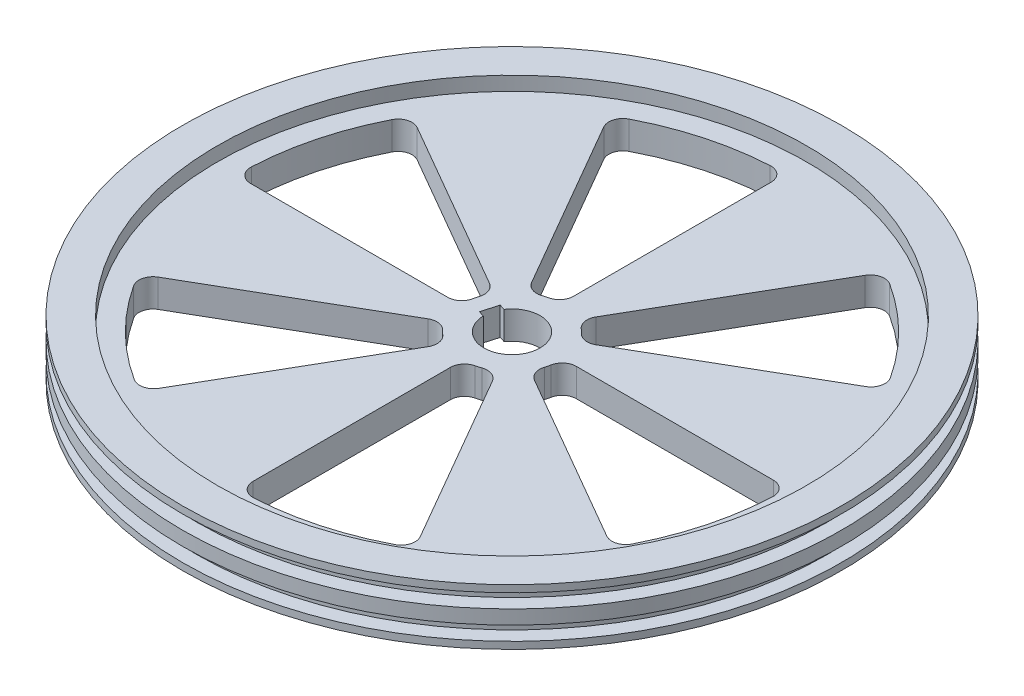
SolidWorks part; units mm, degrees
material "1023 Carbon Steel Sheet (SS)"
ref_plane "Front Plane" through (0, 0, 0) normal (0, 0, 1) x (1, 0, 0)
ref_plane "Top Plane" through (0, 0, 0) normal (0, 1, 0) x (1, 0, 0)
ref_plane "Right Plane" through (0, 0, 0) normal (1, 0, 0) x (0, 0, -1)
sketch "Sketch1" plane through (0, 0, 0) normal (1, 0, 0) x (0, 0, -1)
  line L0 (0, 0) -> (0, 76.2243) construction
  line L1 (20, 0) -> (20, 40)
  line L2 (20, 0) -> (235, 0)
  line L3 (235, 0) -> (235, 5)
  line L4 (235, 5) -> (225, 5)
  line L5 (225, 5) -> (225, 15)
  line L6 (225, 15) -> (235, 15)
  line L7 (235, 15) -> (235, 25)
  line L8 (235, 25) -> (225, 25)
  line L9 (225, 25) -> (225, 35)
  line L10 (225, 35) -> (235, 35)
  line L11 (235, 35) -> (235, 40)
  line L12 (235, 40) -> (20, 40)
  point P11 (225, 30)
  dimension "D1" = 20
  dimension "D2" = 225
revolve "Revolve1" add sketch "Sketch1" angle 360 about L0
sketch "Sketch2" plane through (0, 40, 0) normal (0, 1, 0) x (1, 0, 0)
  line L0 (-19.9952, -0.4393) -> (-24.0488, 0.7384)
  line L7 (-24.0488, 0.7384) -> (-20.7011, 12.2619)
  line L8 (-20.7011, 12.2619) -> (-16.6475, 11.0843)
  arc A2 (-19.9952, -0.4393) -> (-16.6475, 11.0843) centre (0, 0) ccw
  point P0 (0, 21.5959)
extrude "Cut-Extrude1" cut sketch "Sketch2" against normal through all
sketch "Sketch3" plane through (0, 40, 0) normal (0, 1, 0) x (1, 0, 0)
  circle A0 centre (0, 0) radius 210
extrude "Cut-Extrude2" cut sketch "Sketch3" against normal blind 10
sketch "Sketch4" plane through (0, 0, 0) normal (0, -1, 0) x (1, 0, 0)
  circle A0 centre (0, 0) radius 210
extrude "Cut-Extrude3" cut sketch "Sketch4" against normal blind 10
sketch "Sketch5" plane through (0, 10, 0) normal (0, -1, 0) x (1, 0, 0)
  line L0 (0, 43.8748) -> (0, 184.6993)
  line L1 (23.4955, 37.4843) -> (93.78, 159.2207)
  line L2 (44.2101, -1.6055) -> (184.7792, -1.6055)
  line L3 (37.9967, 21.9374) -> (159.9542, 92.3496)
  line L4 (20.7146, -39.0898) -> (90.9991, -160.8262)
  line L5 (37.9967, -21.9374) -> (159.9542, -92.3496)
  line L6 (-23.4955, -37.4843) -> (-93.78, -159.2207)
  line L7 (0, -43.8748) -> (0, -184.6993)
  line L8 (-44.2101, 1.6055) -> (-184.7792, 1.6055)
  line L9 (-37.9967, -21.9374) -> (-159.9542, -92.3496)
  line L10 (-20.7146, 39.0898) -> (-90.9991, 160.8262)
  line L11 (-37.9967, 21.9374) -> (-159.9542, 92.3496)
  arc A0 (11.5385, 33.0433) -> (7.7778, 34.1249) centre (0, 0) ccw
  arc A1 (89.7216, 173.0989) -> (10.5406, 194.6846) centre (0, 0) ccw
  arc A2 (23.4955, 37.4843) -> (11.5385, 33.0433) centre (14.8352, 42.4843) cw
  arc A3 (7.7778, 34.1249) -> (0, 43.8748) centre (10, 43.8748) cw
  arc A4 (93.78, 159.2207) -> (89.7216, 173.0989) centre (85.1198, 164.2207) ccw
  arc A5 (0, 184.6993) -> (10.5406, 194.6846) centre (10, 184.6993) cw
  arc A6 (44.2101, -1.6055) -> (34.3856, 6.529) centre (44.2101, 8.3945) cw
  arc A7 (34.3856, 6.529) -> (33.4419, 10.3267) centre (0, 0) ccw
  arc A8 (33.4419, 10.3267) -> (37.9967, 21.9374) centre (42.9967, 13.2772) cw
  arc A9 (159.9542, 92.3496) -> (173.8721, 88.2139) centre (164.9542, 83.6894) cw
  arc A10 (194.7689, 8.8483) -> (173.8721, 88.2139) centre (0, 0) ccw
  arc A11 (184.7792, -1.6055) -> (194.7689, 8.8483) centre (184.7792, 8.3945) ccw
  arc A12 (20.7146, -39.0898) -> (22.8471, -26.5143) centre (29.3749, -34.0898) cw
  arc A13 (22.8471, -26.5143) -> (25.6641, -23.7982) centre (0, 0) ccw
  arc A14 (25.6641, -23.7982) -> (37.9967, -21.9374) centre (32.9967, -30.5977) cw
  arc A15 (159.9542, -92.3496) -> (163.3315, -106.4708) centre (154.9542, -101.0099) cw
  arc A16 (105.0473, -164.2507) -> (163.3315, -106.4708) centre (0, 0) ccw
  arc A17 (90.9991, -160.8262) -> (105.0473, -164.2507) centre (99.6594, -155.8262) ccw
  arc A18 (-23.4955, -37.4843) -> (-11.5385, -33.0433) centre (-14.8352, -42.4843) cw
  arc A19 (-11.5385, -33.0433) -> (-7.7778, -34.1249) centre (0, 0) ccw
  arc A20 (-7.7778, -34.1249) -> (0, -43.8748) centre (-10, -43.8748) cw
  arc A21 (0, -184.6993) -> (-10.5406, -194.6846) centre (-10, -184.6993) cw
  arc A22 (-89.7216, -173.0989) -> (-10.5406, -194.6846) centre (0, 0) ccw
  arc A23 (-93.78, -159.2207) -> (-89.7216, -173.0989) centre (-85.1198, -164.2207) ccw
  arc A24 (-44.2101, 1.6055) -> (-34.3856, -6.529) centre (-44.2101, -8.3945) cw
  arc A25 (-34.3856, -6.529) -> (-33.4419, -10.3267) centre (0, 0) ccw
  arc A26 (-33.4419, -10.3267) -> (-37.9967, -21.9374) centre (-42.9967, -13.2772) cw
  arc A27 (-159.9542, -92.3496) -> (-173.8721, -88.2139) centre (-164.9542, -83.6894) cw
  arc A28 (-194.7689, -8.8483) -> (-173.8721, -88.2139) centre (0, 0) ccw
  arc A29 (-184.7792, 1.6055) -> (-194.7689, -8.8483) centre (-184.7792, -8.3945) ccw
  arc A30 (-20.7146, 39.0898) -> (-22.8471, 26.5143) centre (-29.3749, 34.0898) cw
  arc A31 (-22.8471, 26.5143) -> (-25.6641, 23.7982) centre (0, 0) ccw
  arc A32 (-25.6641, 23.7982) -> (-37.9967, 21.9374) centre (-32.9967, 30.5977) cw
  arc A33 (-159.9542, 92.3496) -> (-163.3315, 106.4708) centre (-154.9542, 101.0099) cw
  arc A34 (-105.0473, 164.2507) -> (-163.3315, 106.4708) centre (0, 0) ccw
  arc A35 (-90.9991, 160.8262) -> (-105.0473, 164.2507) centre (-99.6594, 155.8262) ccw
  point P11 (0, 35)
  point P78 (0, 0)
  dimension "D1" = 30
  dimension "D2" = 10
  dimension "D3" = 6
extrude "Cut-Extrude4" cut sketch "Sketch5" against normal through all
